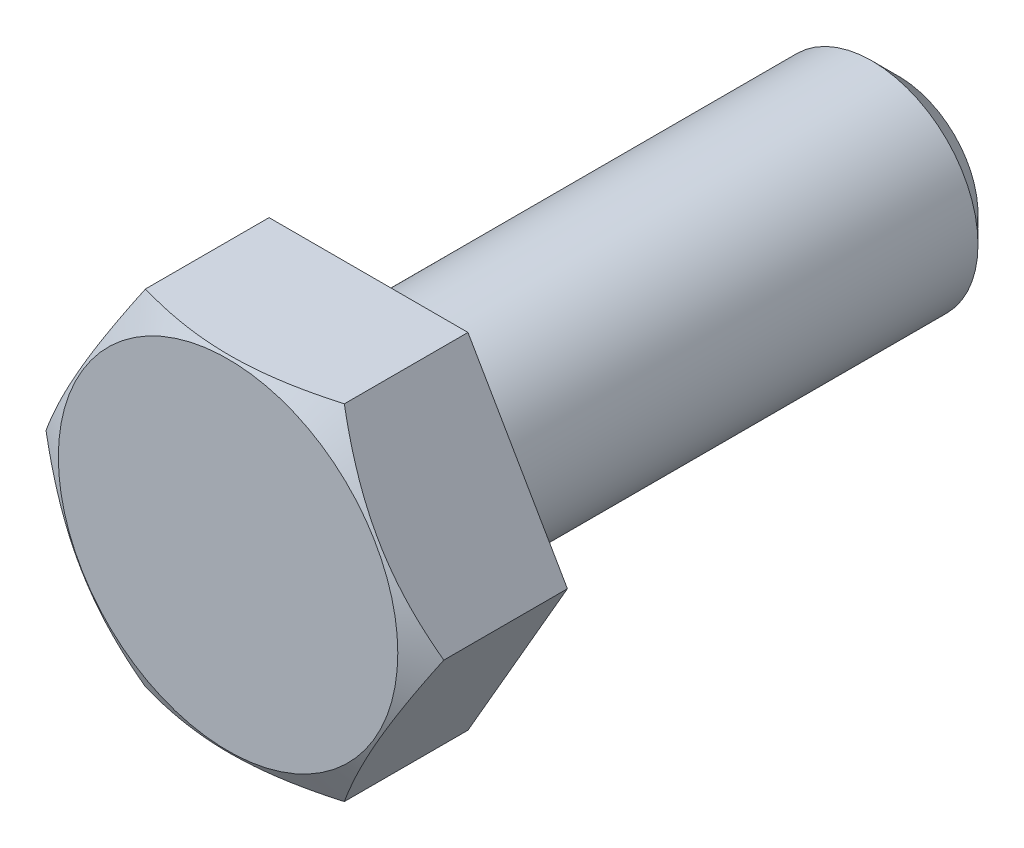
SolidWorks part; units mm, degrees
material "1.0117 (S235J2G4)"
ref_plane "Спереди" through (0, 0, 0) normal (0, 0, 1) x (1, 0, 0)
ref_plane "Сверху" through (0, 0, 0) normal (0, 1, 0) x (1, 0, 0)
ref_plane "Справа" through (0, 0, 0) normal (1, 0, 0) x (0, 0, -1)
sketch "Эскиз1" plane through (0, 0, 0) normal (0, 0, 1) x (1, 0, 0)
  line L1 (7.5056, 0) -> (3.7528, 6.5)
  line L2 (3.7528, 6.5) -> (-3.7528, 6.5)
  line L3 (-3.7528, 6.5) -> (-7.5056, 0)
  line L4 (-7.5056, 0) -> (-3.7528, -6.5)
  line L5 (-3.7528, -6.5) -> (3.7528, -6.5)
  line L6 (3.7528, -6.5) -> (7.5056, 0)
  circle A0 centre (0, 0) radius 6.5 construction
  dimension "D1" = 13
extrude "Бобышка-Вытянуть1" add sketch "Эскиз1" along normal blind 5.3
sketch "Эскиз2" plane through (0, 0, 0) normal (0, 0, -1) x (-1, 0, 0)
  circle A0 centre (0, 0) radius 4
  dimension "D1" = 8
extrude "Бобышка-Вытянуть2" add sketch "Эскиз2" along normal blind 20
chamfer "Фаска1" distance 1 angle 45 1 edges at (-4, 0, -20)
sketch "Эскиз3" plane through (0, 0, 0) normal (0, 1, 0) x (1, 0, 0)
  line L0 (-12.5056, -1.7782) -> (-6.4056, -5.3)
  line L1 (0, -5.3) -> (0, 0) construction
  line L2 (-6.4056, -5.3) -> (-12.5056, -5.3)
  line L3 (-12.5056, -5.3) -> (-12.5056, -1.7782)
  line L5 (3.7528, -5.3) -> (-3.7528, -5.3) construction
  line L6 (-7.5056, -5.3) -> (-7.5056, 0) construction
  line L7 (-3.7528, -5.3) -> (-7.5056, -5.3) construction
  dimension "D1" = 1.1
  dimension "D4" = 5
  dimension "D5" = 30
revolve "Вырез-Повернуть1" cut sketch "Эскиз3" angle 360 about L1
